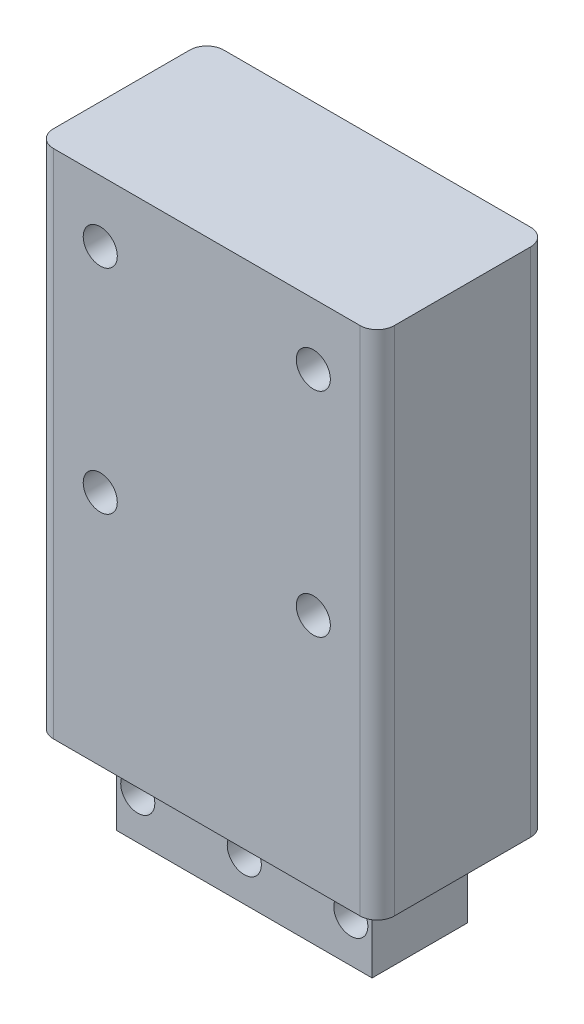
SolidWorks part; units mm, degrees
ref_plane "Front Plane" through (0, 0, 0) normal (0, 0, 1) x (1, 0, 0)
ref_plane "Top Plane" through (0, 0, 0) normal (0, 1, 0) x (1, 0, 0)
ref_plane "Right Plane" through (0, 0, 0) normal (1, 0, 0) x (0, 0, -1)
sketch "Sketch1" plane through (0, 0, 0) normal (0, 1, 0) x (1, 0, 0)
  line L1 (20, 10) -> (-20, 10)
  line L2 (20, 10) -> (20, -10)
  line L3 (20, -10) -> (-20, -10)
  line L4 (-20, 10) -> (-20, -10)
  line L5 (20, 10) -> (-20, -10) construction
  line L6 (20, -10) -> (-20, 10) construction
  point P0 (0, 0)
  dimension "D1" = 40
  dimension "D2" = 20
extrude "Boss-Extrude1" add sketch "Sketch1" against normal blind 20
sketch "Sketch3" plane through (0, 0, 0) normal (0, 1, 0) x (1, 0, 0)
  line L1 (20, -10) -> (20, 10) construction
  line L3 (-20, 10) -> (20, 10)
  line L4 (-20, 10) -> (-20, -10)
  line L6 (-20, -10) -> (20, -10) construction
  line L8 (20, 10) -> (-20, 10) construction
  line L9 (0, 0) -> (0, 37.8054) construction
  line L10 (-20, -10) -> (20, -10)
  line L11 (20, 10) -> (20, -10)
  line L12 (-20, 10) -> (20, -10) construction
  line L13 (-20, -10) -> (20, 10) construction
  point P16 (0, -10)
  point P17 (0, 10)
extrude "Boss-Extrude2" add sketch "Sketch3" along normal blind 40
sketch "Sketch4" plane through (0, -20, 0) normal (0, -1, 0) x (1, 0, 0)
  line L2 (-28.4286, 0) -> (27.9574, 0) construction
  line L3 (0, 25.4656) -> (0, -18.2483) construction
  line L12 (-15, 5.6) -> (-15, -5.6)
  line L13 (-15, -5.6) -> (15, -5.6)
  line L14 (15, -5.6) -> (15, 5.6)
  line L15 (15, 5.6) -> (-15, 5.6)
  dimension "D1" = 11.2
  dimension "D2" = 30
extrude "Boss-Extrude3" add sketch "Sketch4" along normal blind 10
sketch "Sketch5" plane through (0, 0, -5.6) normal (0, 0, -1) x (-1, 0, 0)
  line L0 (-20, -20) -> (20, -20) construction
  line L1 (0, -25) -> (0, 0.8185) construction
  circle A0 centre (0, -25) radius 2
  circle A1 centre (12.5, -25) radius 2
  circle A2 centre (-12.5, -25) radius 2
  dimension "D1" = 4
  dimension "D3" = 4
  dimension "D2" = 5
  dimension "D4" = 25
extrude "Cut-Extrude1" cut sketch "Sketch5" against normal mid plane 70
sketch "Sketch6" plane through (0, 0, -10) normal (0, 0, -1) x (-1, 0, 0)
  line L0 (0, 0) -> (0, 96.9628) construction
  line L1 (-20, 40) -> (20, 40) construction
  line L2 (20, -20) -> (20, 40) construction
  circle A0 centre (12.5, 7.8008) radius 2
  circle A1 centre (12.5, 32.8008) radius 2
  circle A2 centre (-12.5, 32.8008) radius 2
  circle A3 centre (-12.5, 7.8008) radius 2
  dimension "D1" = 4
  dimension "D3" = 4
  dimension "D2" = 25
  dimension "D4" = 25
  dimension "D5" = 7.1992
  dimension "D6" = 7.5
extrude "Cut-Extrude2" cut sketch "Sketch6" against normal blind 35
fillet "Fillet2" radius 2 4 edges at (20, 10, -10) (20, 10, 10) (-20, 10, 10) (-20, 10, -10)
